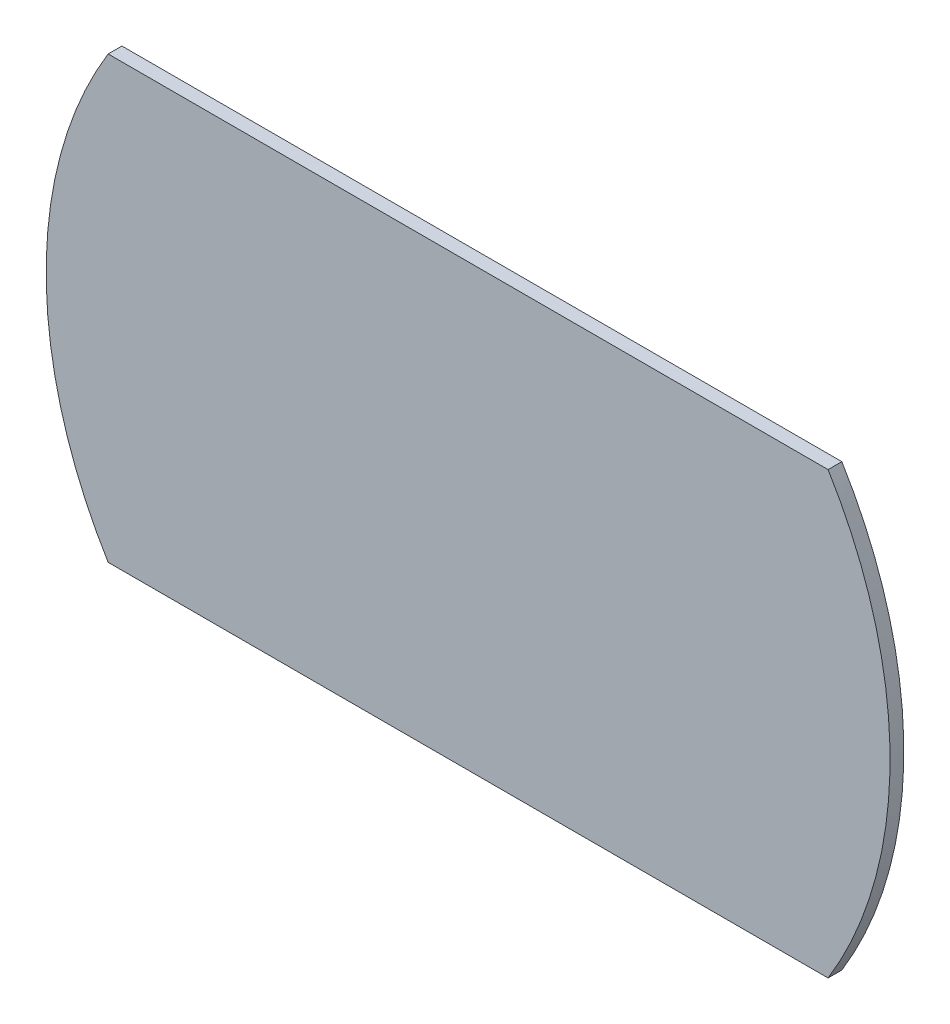
SolidWorks part; units mm, degrees
ref_plane "Front Plane" through (0, 0, 0) normal (0, 0, 1) x (1, 0, 0)
ref_plane "Top Plane" through (0, 0, 0) normal (0, 1, 0) x (1, 0, 0)
ref_plane "Right Plane" through (0, 0, 0) normal (1, 0, 0) x (0, 0, -1)
sketch "Sketch1" plane through (0, 0, 0) normal (0, 0, 1) x (1, 0, 0)
  line L1 (-498.384, 304.8) -> (498.384, 304.8)
  line L3 (-498.384, -304.8) -> (498.384, -304.8)
  arc A0 (-498.384, 304.8) -> (-498.384, -304.8) centre (0, 0) ccw
  arc A1 (498.384, -304.8) -> (498.384, 304.8) centre (0, 0) ccw
  point P7 (0, 0)
  dimension "D1" = 1168.4
  dimension "D2" = 609.6
  dimension "D3" = 304.8
extrude "Boss-Extrude1" add sketch "Sketch1" along normal blind 19.05
